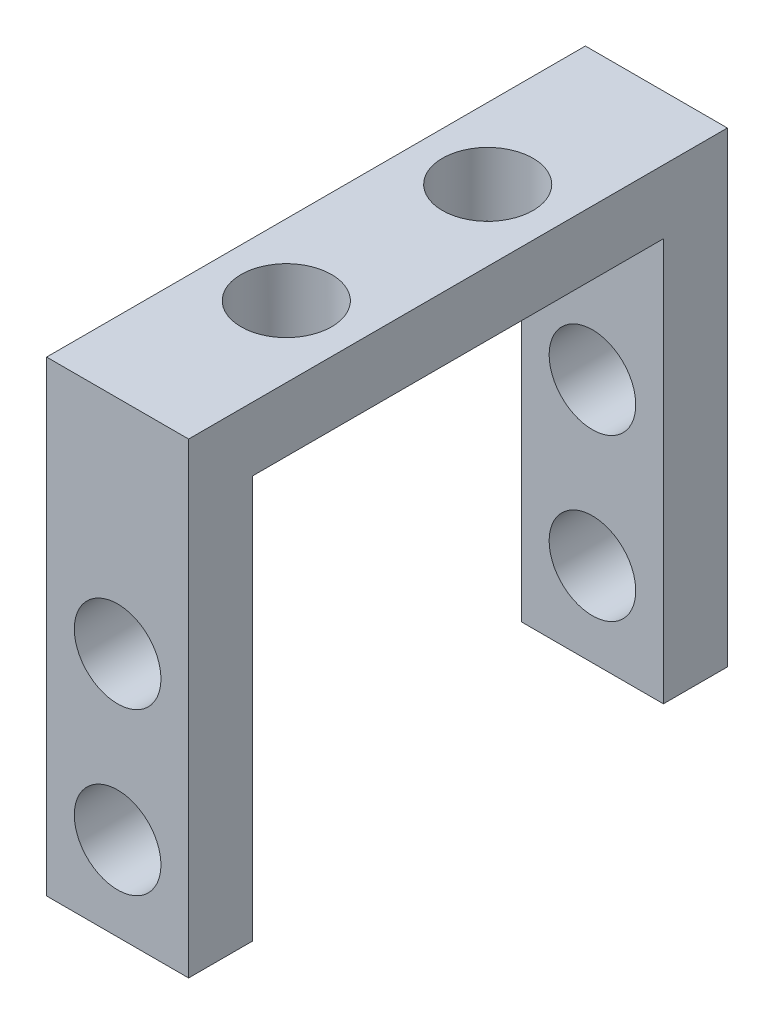
SolidWorks part; units mm, degrees
ref_plane "Front Plane" through (0, 0, 0) normal (0, 0, 1) x (1, 0, 0)
ref_plane "Top Plane" through (0, 0, 0) normal (0, 1, 0) x (1, 0, 0)
ref_plane "Right Plane" through (0, 0, 0) normal (1, 0, 0) x (0, 0, -1)
sketch "Sketch2" plane through (0, 0, 0) normal (0, 1, 0) x (1, 0, 0)
  line L1 (-3.525, 13.375) -> (3.525, 13.375)
  line L2 (-3.525, 13.375) -> (-3.525, -13.375)
  line L3 (-3.525, -13.375) -> (3.525, -13.375)
  line L4 (3.525, 13.375) -> (3.525, -13.375)
  line L5 (-3.525, 13.375) -> (3.525, -13.375) construction
  line L6 (-3.525, -13.375) -> (3.525, 13.375) construction
  point P0 (0, 0)
  dimension "D1" = 7.05
  dimension "D2" = 26.75
extrude "Boss-Extrude1" add sketch "Sketch2" along normal blind 3.175
sketch "Sketch3" plane through (0, 0, 0) normal (0, -1, 0) x (1, 0, 0)
  line L0 (3.525, 0) -> (-3.525, 0) construction
  line L1 (3.525, 13.375) -> (3.525, -13.375) construction
  line L2 (-3.525, -13.375) -> (-3.525, 13.375) construction
  line L3 (-3.525, 13.375) -> (-3.525, 10.2)
  line L4 (3.525, -13.375) -> (-3.525, -13.375)
  line L5 (3.525, -13.375) -> (3.525, -10.2)
  line L6 (3.525, -10.2) -> (-3.525, -10.2)
  line L7 (-3.525, -13.375) -> (-3.525, -10.2)
  line L8 (3.525, 10.2) -> (-3.525, 10.2)
  line L9 (3.525, 13.375) -> (3.525, 10.2)
  line L10 (3.525, 13.375) -> (-3.525, 13.375)
  dimension "D1" = 3.175
extrude "Boss-Extrude2" add sketch "Sketch3" along normal blind 20
sketch "Sketch4" plane through (0, 3.175, 0) normal (0, 1, 0) x (1, 0, 0)
  line L0 (-3.525, 0) -> (3.525, 0) construction
  line L1 (-3.525, 13.375) -> (-3.525, -13.375) construction
  line L2 (3.525, -13.375) -> (3.525, 13.375) construction
  line L3 (0, 0) -> (0, 13.375) construction
  line L4 (3.525, 13.375) -> (-3.525, 13.375) construction
  circle A0 centre (0, 5) radius 2.25
  circle A1 centre (0, -5) radius 2.25
  dimension "D1" = 4.5
  dimension "D2" = 5
extrude "Cut-Extrude1" cut sketch "Sketch4" against normal up to surface (3.175 mm away) up to face at (0, 0, 0)
sketch "Sketch5" plane through (0, 0, -13.375) normal (0, 0, -1) x (-1, 0, 0)
  line L0 (0, 3.175) -> (0, -20) construction
  line L1 (-3.525, 3.175) -> (3.525, 3.175) construction
  line L2 (3.525, -20) -> (-3.525, -20) construction
  circle A0 centre (0, -7.825) radius 2.15
  circle A1 centre (0, -15.825) radius 2.15
  dimension "D1" = 4.3
  dimension "D2" = 8
  dimension "D3" = 11
extrude "Cut-Extrude2" cut sketch "Sketch5" against normal through all
